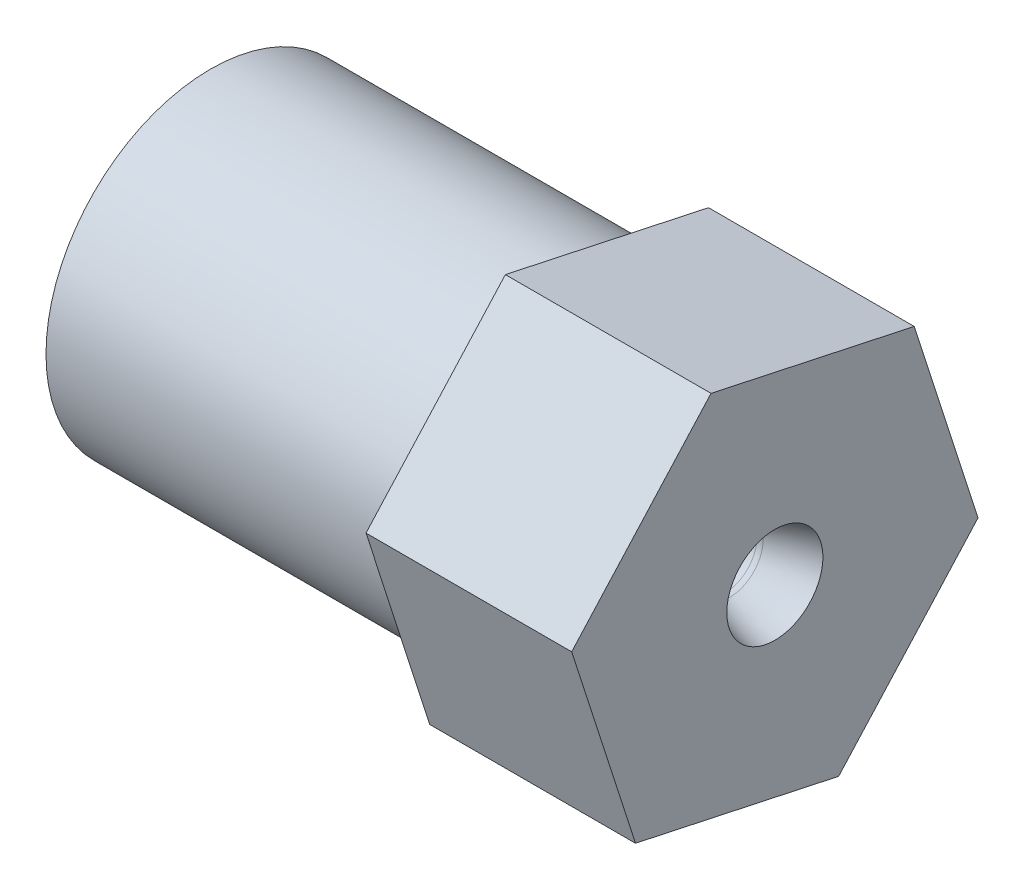
SolidWorks part; units mm, degrees
ref_plane "Front Plane" through (0, 0, 0) normal (0, 0, 1) x (1, 0, 0)
ref_plane "Top Plane" through (0, 0, 0) normal (0, 1, 0) x (1, 0, 0)
ref_plane "Right Plane" through (0, 0, 0) normal (1, 0, 0) x (0, 0, -1)
sketch "Sketch1" plane through (0, 0, 0) normal (0, 0, 1) x (1, 0, 0)
  line L0 (0, 0) -> (3.0977, 0) construction
  line L1 (0.3126, 2.0636) -> (3.0977, 3.2458) construction
  line L2 (-2.1213, 2.8787) -> (-2.7577, 3.5151)
  line L3 (-31.75, 4.445) -> (-31.75, 10.16) construction
  line L4 (-5.0028, 4.445) -> (-31.75, 4.445) construction
  line L5 (-31.75, 10.16) -> (-9.6023, 10.16)
  line L6 (3.0977, 10.16) -> (3.0977, 2.9665)
  line L7 (3.0977, 2.9665) -> (12.7016, 5.1837) construction
  line L8 (-9.6023, 10.16) -> (3.0977, 10.16)
  line L9 (-5.0028, 4.445) -> (-13.462, 4.445)
  line L10 (-19.939, 5.461) -> (-19.939, 6.8199)
  line L11 (-20.066, 6.9469) -> (-24.892, 6.9469)
  line L12 (-24.892, 6.9469) -> (-24.892, 7.8994)
  line L13 (-25.019, 8.0264) -> (-31.115, 8.0264)
  line L14 (-31.75, 10.16) -> (-31.75, 8.6614)
  line L15 (0, 0) -> (-31.75, 0) construction
  line L16 (-13.462, 4.445) -> (-13.462, 4.699)
  line L17 (-13.589, 4.826) -> (-19.304, 4.826)
  arc A0 (-2.1213, 2.8787) -> (0, 2) centre (0, 5) ccw
  arc A1 (0, 2) -> (0.3126, 2.0636) centre (0, 2.8) ccw
  arc A2 (-2.7577, 3.5151) -> (-5.0028, 4.445) centre (-5.0028, 1.27) ccw
  arc A3 (-31.115, 8.0264) -> (-31.75, 8.6614) centre (-31.115, 8.6614) cw
  arc A4 (-19.304, 4.826) -> (-19.939, 5.461) centre (-19.304, 5.461) cw
  arc A5 (-13.462, 4.699) -> (-13.589, 4.826) centre (-13.589, 4.699) ccw
  arc A6 (-19.939, 6.8199) -> (-20.066, 6.9469) centre (-20.066, 6.8199) ccw
  arc A7 (-24.892, 7.8994) -> (-25.019, 8.0264) centre (-25.019, 7.8994) ccw
  parabola Q0 (3.0977, 2.9665) -> (0.3126, 2.0636) focus (3.544, -5.5492) apex (0.3126, 2.0636)
  point P30 (-31.75, 8.0264)
  point P39 (-24.892, 8.0264)
  dimension "D3" = 3
  dimension "D4" = 0.8
  dimension "D11" = 3.175
  dimension "D12" = 13
  dimension "D14" = 6.9469
  dimension "D20" = 0.635
  dimension "D21" = 0.127
  dimension "D2" = 3.0977
  dimension "D5" = 2.9665
  dimension "D6" = 23
  dimension "D7" = 45
  dimension "D8" = 8.0264
  dimension "D9" = 31.75
  dimension "D10" = 10.16
  dimension "D13" = 12.7
  dimension "D15" = 4.445
  dimension "D16" = 6.858
  dimension "D17" = 11.811
  dimension "D18" = 18.288
  dimension "D19" = 4.826
  dimension "D22" = 2
revolve "Revolve1" add sketch "Sketch1" angle 360 about L0
sketch "Sketch4" plane through (3.0977, 0, 0) normal (1, 0, 0) x (0, 0, -1)
  line L1 (3.9404, -12.2116) -> (12.5458, -2.6933)
  line L2 (12.5458, -2.6933) -> (8.6054, 9.5183)
  line L3 (8.6054, 9.5183) -> (-3.9404, 12.2116)
  line L4 (-3.9404, 12.2116) -> (-12.5458, 2.6933)
  line L5 (-12.5458, 2.6933) -> (-8.6054, -9.5183)
  line L6 (-8.6054, -9.5183) -> (3.9404, -12.2116)
  circle A0 centre (0, 0) radius 10.16
  circle A1 centre (0, 0) radius 10.16 construction
  circle A2 centre (0, 0) radius 11.1125 construction
  circle M1 centre (0, 0) radius 10.16
  dimension "D1" = 22.225
extrude "Boss-Extrude1" add sketch "Sketch4" against normal blind 12.7 contours L4 L5 M1 | L3 L4 M1 | L2 L3 M1 | L1 L2 M1 | L6 L1 M1 | L5 L6 M1
fillet "Fillet1" radius 0.635 1 edges at (-9.6023, 0, -10.16)
equation "\"D3@Sketch1\" = 1.5 * \"D22@Sketch1\""
equation "\"D4@Sketch1\"  = .4 * \"D22@Sketch1\""
equation "\"D5@Sketch1\"=\"D22@Sketch1\" * ( \"er\") ^ .5"
equation "\"er\"= 2.2"
